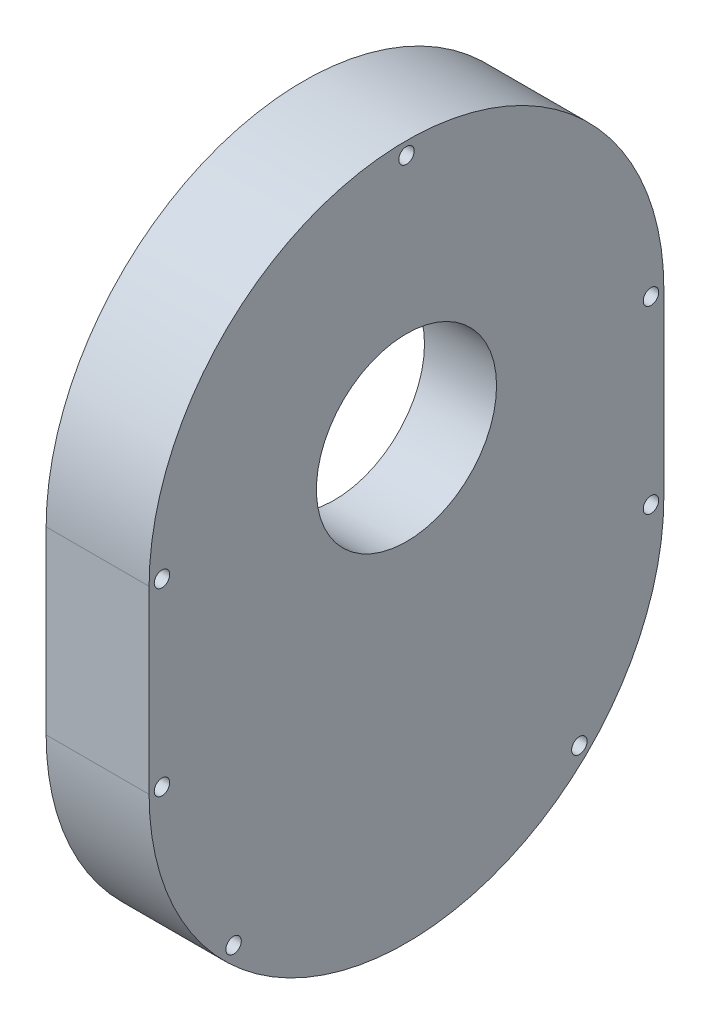
SolidWorks part; units mm, degrees
ref_plane "Alzado" through (0, 0, 0) normal (0, 0, 1) x (1, 0, 0)
ref_plane "Planta" through (0, 0, 0) normal (0, 1, 0) x (1, 0, 0)
ref_plane "Vista lateral" through (0, 0, 0) normal (1, 0, 0) x (0, 0, -1)
sketch "Croquis1" plane through (0, 0, 0) normal (1, 0, 0) x (0, 0, -1)
  line L0 (-50, 35) -> (-50, 0)
  line L1 (50, 35) -> (50, 0)
  arc A0 (-50, 0) -> (50, 0) centre (0, 0) ccw
  arc A1 (50, 35) -> (-50, 35) centre (0, 35) ccw
  circle A2 centre (0, 35) radius 17.5
  dimension "D1" = 100
  dimension "D3" = 35
  dimension "D2" = 35
extrude "Saliente-Extruir1" add sketch "Croquis1" along normal blind 20
sketch "Croquis2" plane through (0, 0, 0) normal (1, 0, 0) x (0, 0, -1)
  circle A0 centre (0, 35) radius 30
  dimension "D1" = 60
extrude "Cortar-Extruir1" cut sketch "Croquis2" along normal blind 6
ref_plane "Plano1" through (0, -50, 0) normal (0, 1, 0) x (1, 0, 0)
sketch "Croquis3" plane through (0, -50, 0) normal (0, 1, 0) x (1, 0, 0)
  line L0 (20, 0) -> (-35, 0) construction
  line L1 (0, 0) -> (0, 19.6434) construction
  line L2 (0, 50) -> (0, -50) construction
  line L3 (20, -50) -> (20, 50) construction
  circle A2 centre (-7.5, 0) radius 10
  point P1 (-7.5, 0)
  dimension "D1" = 55
  dimension "D2" = 20
extrude "Cortar-Extruir2" cut sketch "Croquis3" along normal blind 10
sketch "Croquis4" plane through (0, 0, 0) normal (-1, 0, 0) x (0, 0, 1)
  circle A0 centre (0, 35) radius 47.5 construction
  circle A1 centre (0, 0) radius 47.5 construction
  circle A2 centre (0, 82.5) radius 1.5
  circle A3 centre (47.5, 35) radius 1.5
  circle A4 centre (0, -12.5) radius 1.5 construction
  circle A5 centre (-47.5, 35) radius 1.5
  circle A6 centre (-47.5, 0) radius 1.5
  circle A7 centre (-33.5876, 33.5876) radius 1.5 construction
  circle A8 centre (0, 47.5) radius 1.5 construction
  circle A9 centre (33.5876, 33.5876) radius 1.5 construction
  circle A10 centre (47.5, 0) radius 1.5
  circle A11 centre (33.5876, -33.5876) radius 1.5
  circle A12 centre (0, -47.5) radius 1.5 construction
  circle A13 centre (-33.5876, -33.5876) radius 1.5
  point P17 (0, 35)
  point P33 (0, 0)
  dimension "D1" = 95
  dimension "D2" = 95
  dimension "D3" = 3
  dimension "D4" = 3
  dimension "D6" = 4
  dimension "D5" = 8
extrude "Cortar-Extruir3" cut sketch "Croquis4" against normal through all
